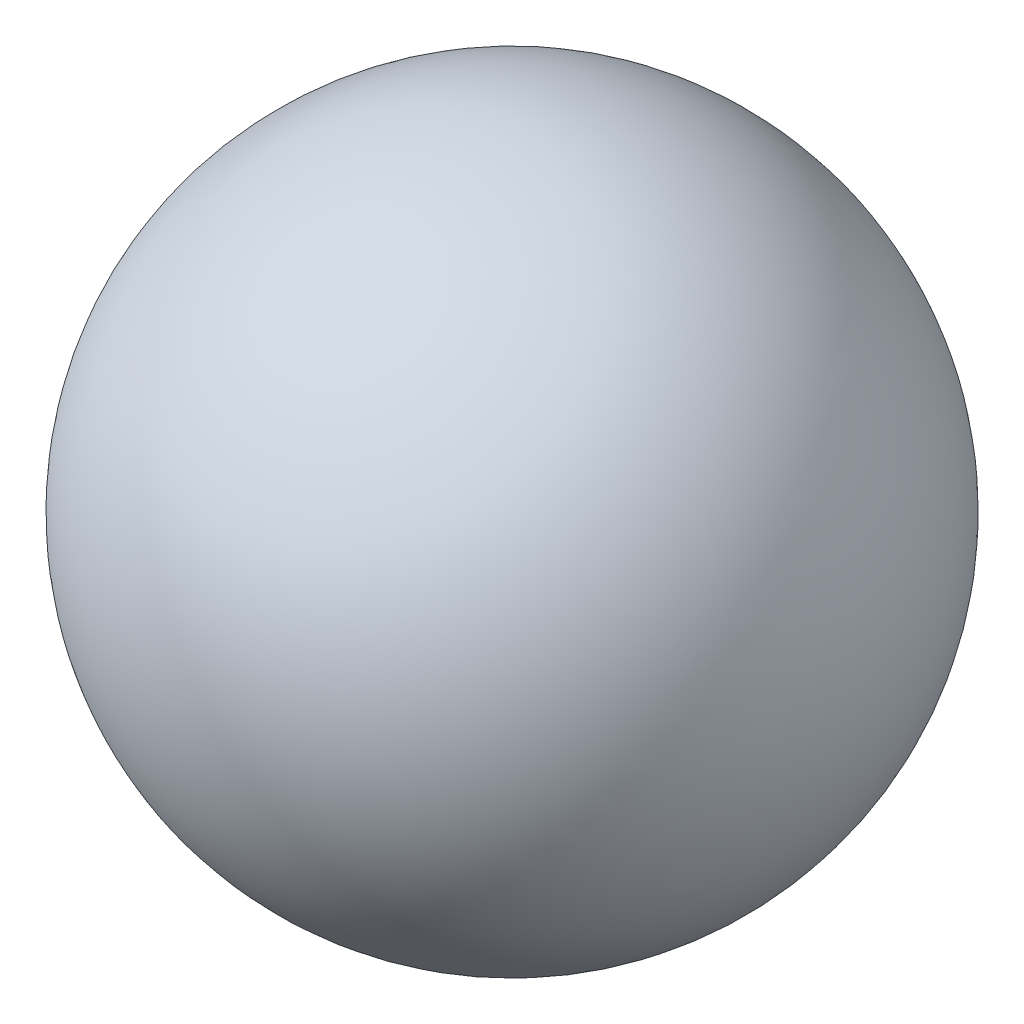
SolidWorks part; units mm, degrees
ref_plane "Front Plane" through (0, 0, 0) normal (0, 0, 1) x (1, 0, 0)
ref_plane "Top Plane" through (0, 0, 0) normal (0, 1, 0) x (1, 0, 0)
ref_plane "Right Plane" through (0, 0, 0) normal (1, 0, 0) x (0, 0, -1)
sketch "Sketch1" plane through (0, 0, 0) normal (0, 1, 0) x (1, 0, 0)
  line L0 (0, 0) -> (0, -28.575)
  line L1 (0, 0) -> (0, 28.575)
  arc A1 (0, -28.575) -> (0, 28.575) centre (0, 0) ccw
revolve "Revolve1" add sketch "Sketch1" angle 360 about L1
